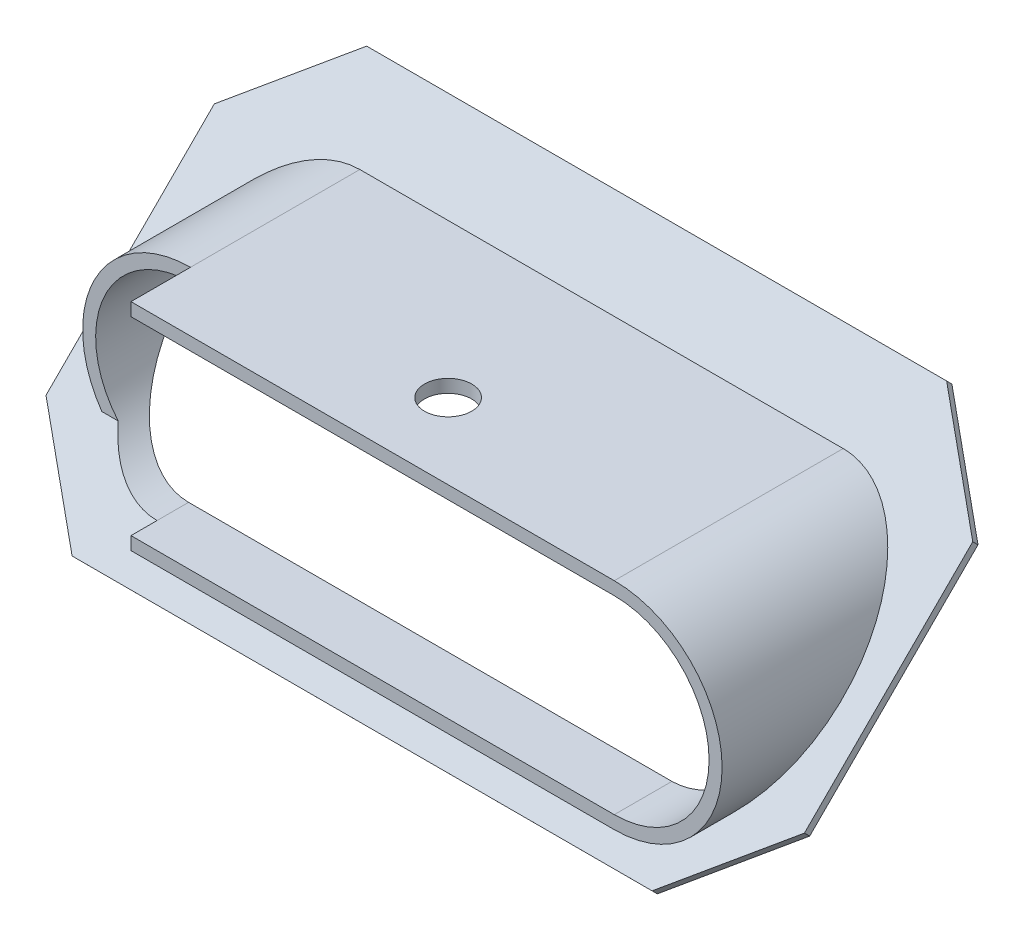
SolidWorks part; units mm, degrees
ref_plane "Front Plane" through (0, 0, 0) normal (0, 0, 1) x (1, 0, 0)
ref_plane "Top Plane" through (0, 0, 0) normal (0, 1, 0) x (1, 0, 0)
ref_plane "Right Plane" through (0, 0, 0) normal (1, 0, 0) x (0, 0, -1)
sketch "Sketch22" plane through (0, 0, 0) normal (0, 0, 1) x (1, 0, 0)
  line L3 (32.5, 0) -> (-32.5, 0) construction
  line L10 (32.5, -14.5) -> (-32.5, -14.5)
  line L11 (32.5, 14.5) -> (-32.5, 14.5)
  arc A2 (32.5, -14.5) -> (32.5, 14.5) centre (32.5, 0) ccw
  arc A3 (-32.5, 14.5) -> (-32.5, -14.5) centre (-32.5, 0) ccw
  point P8 (0, 0)
  point P15 (0, 0)
extrude "Boss-Extrude12" add sketch "Sketch22" along normal blind 80
sketch "Sketch34" plane through (0, 0, 0) normal (0, 0, -1) x (-1, 0, 0)
  line L0 (32.5, -14.5) -> (32.5, 14.5) construction
ref_plane "Plane5" through (-32.5, 0, 0) normal (1, 0, 0) x (0, 0, -1)
sketch "Sketch35" plane through (-32.5, 0, 0) normal (1, 0, 0) x (0, 0, -1)
  line L0 (0, 14.5) -> (-29.0269, -14.5)
  line L1 (-80, -14.5) -> (0, -14.5) construction
  line L2 (-29.0269, -14.5) -> (0, -14.5)
  line L3 (0, -14.5) -> (0, 14.5)
extrude "Cut-Extrude10" cut sketch "Sketch35" against normal through all and the other way through all
ref_plane "Plane6" through (0, 7.2567, 7.25) normal (0, -0.7074, -0.7068) x (-1, 0, 0)
sketch "Sketch37" plane through (0, 7.2567, 7.25) normal (0, -0.7074, -0.7068) x (-1, 0, 0)
  line L0 (0, 10.2483) -> (0, -30.7829) construction
  line L1 (-32.5, 10.2483) -> (32.5, 10.2483) construction
  line L2 (32.5, -30.7829) -> (-32.5, -30.7829) construction
  line L4 (51, 17.7327) -> (-51, 17.7327)
  line L5 (51, 17.7327) -> (51, -38.2673)
  line L6 (51, -38.2673) -> (-51, -38.2673)
  line L7 (-51, 17.7327) -> (-51, -38.2673)
  line L8 (51, 17.7327) -> (-51, -38.2673) construction
  line L9 (51, -38.2673) -> (-51, 17.7327) construction
  point P6 (0, -10.2673)
extrude "Boss-Extrude16" add sketch "Sketch37" against normal blind 3
sketch "Sketch38" plane through (0, 0, 80) normal (0, 0, 1) x (1, 0, 0)
  line L0 (32.5, -14.5) -> (32.5, 14.5)
  line L1 (-32.5, 0) -> (32.5, 0) construction
  line L2 (-32.5, 12.75) -> (32.5, 12.75)
  line L3 (-32.5, -12.75) -> (32.5, -12.75)
  arc A0 (-32.5, 12.75) -> (-32.5, -12.75) centre (-32.5, 0) ccw
  arc A1 (32.5, -12.75) -> (32.5, 12.75) centre (32.5, 0) ccw
  point P6 (0, 0)
extrude "Cut-Extrude11" cut sketch "Sketch38" against normal through all contours L3 A1 L2 A0
sketch "Sketch40" plane through (0, -12.75, 0) normal (0, 1, 0) x (1, 0, 0)
  line L0 (32.5, -27.2752) -> (32.5, -35.025) construction
  line L1 (32.5, -27.2752) -> (32.5, -80) construction
  line L2 (-32.5, -27.2752) -> (-32.5, -35.025) construction
  line L3 (-32.5, -27.2752) -> (-32.5, -80) construction
  line L4 (-32.5, -35.025) -> (32.5, -35.025) construction
  line L6 (69.7281, -35.025) -> (-57.7587, -35.025)
  line L7 (-57.7587, -35.025) -> (-57.7587, -89.8582)
  line L8 (-57.7587, -89.8582) -> (69.7281, -89.8582)
  line L9 (69.7281, -89.8582) -> (69.7281, -35.025)
extrude "Cut-Extrude12" cut sketch "Sketch40" along normal through all and the other way up to surface other way up to face at (0, -14.5, 56.6357)
sketch "Sketch42" plane through (-51, 0, 0) normal (-1, 0, 0) x (0, 0, 1)
  line L0 (35.025, 14.5) -> (27.025, 14.5)
  line L1 (35.025, 14.5) -> (4.2446, 14.5) construction
  line L2 (27.025, 14.5) -> (27.025, -8.2593)
  line L3 (36.4419, -17.6675) -> (-3.1744, 21.9121) construction
  line L4 (27.025, -8.2593) -> (33.2715, -14.5)
  line L5 (33.2715, -14.5) -> (35.025, -14.5)
  line L6 (35.025, -14.5) -> (35.025, 14.5)
extrude "Cut-Extrude14" cut sketch "Sketch42" against normal up to vertex (18.5 mm away) up to point (-32.5, -12.75, 35.025)
hole_wizard "1/4 (0.25) Diameter Hole1" positions "Sketch46" profile "Sketch48" hole size "1/4" standard "ANSI Inch"
sketch "Sketch46" plane through (0, 14.5, 0) normal (0, 1, 0) x (1, 0, 0)
  point P2 (0, -24.875)
sketch "Sketch48" plane through (0, 14.5, 24.875) normal (1, 0, 0) x (0, 0, 1)
  line L0 (0, 0) -> (0, 6.9077)
  line L1 (0, 6.9077) -> (3.175, 5)
  line L2 (3.175, 5) -> (3.175, 0)
  line L5 (3.175, 0) -> (0, 0)
  line L10 (0, 6.9077) -> (-3.175, 5) construction
  line L11 (0, -6.35) -> (0, 107.95) construction
  dimension "Hole Dia." = 6.35
  dimension "Hole Depth" = 5
  dimension "Drill Angle" = 118
chamfer "Chamfer2" distance 12 angle 45 4 edges at (-51, 20.851, -4.2346) (51, 20.851, -4.2346) (51, -18.7287, 35.3818) (-51, -18.7287, 35.3818)
chamfer "Chamfer3" distance 2 angle 45 8 edges at (45, -15.5491, 30.077) (51, 0, 14.5134) (45, 15.5491, -1.0501) (0, 19.7898, -5.2947) (0, -19.7898, 34.3216) (-45, -15.5491, 30.077) (-51, 0, 14.5134) (-45, 15.5491, -1.0501)
sketch "Sketch49" plane through (0, 12.75, 0) normal (0, -1, 0) x (-1, 0, 0)
  line L0 (0, -1.7516) -> (0, -35.025)
  line L1 (32.5, -1.7516) -> (-32.5, -1.7516) construction
  line L2 (-32.5, -35.025) -> (32.5, -35.025) construction
